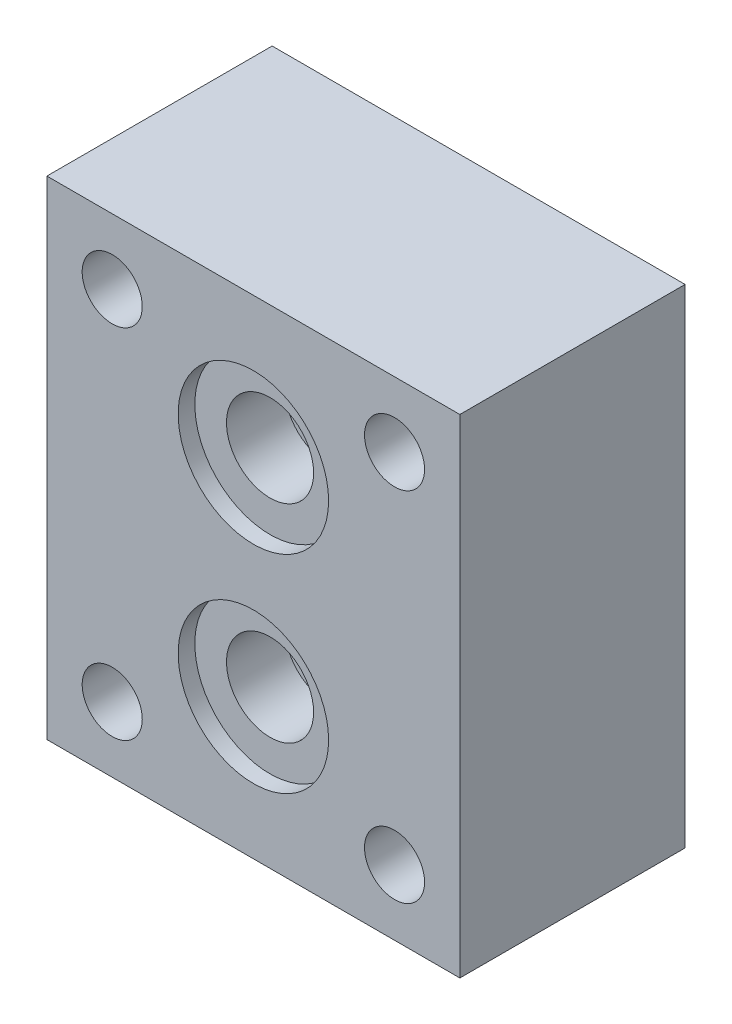
SolidWorks part; units mm, degrees
ref_plane "Front Plane" through (0, 0, 0) normal (1, 0, 0) x (0, 1, 0)
ref_plane "Top Plane" through (0, 0, 0) normal (0, 0, 1) x (0, 1, 0)
ref_plane "Right Plane" through (0, 0, 0) normal (0, 1, 0) x (-1, 0, 0)
sketch "Sketch1" plane through (0, 0, 0) normal (0, 0, 1) x (0, 1, 0)
  line L1 (-41.275, -34.925) -> (41.275, -34.925)
  line L2 (-41.275, -34.925) -> (-41.275, 34.925)
  line L3 (-41.275, 34.925) -> (41.275, 34.925)
  line L4 (41.275, -34.925) -> (41.275, 34.925)
  line L5 (-41.275, -34.925) -> (41.275, 34.925) construction
  line L6 (-41.275, 34.925) -> (41.275, -34.925) construction
  point P0 (0, 0)
extrude "Boss-Extrude1" add sketch "Sketch1" along normal mid plane 38.1
sketch "Sketch2" plane through (0, 0, 0) normal (0, 0, 1) x (0, 1, 0)
  circle A0 centre (-30.226, -23.876) radius 5.08
extrude "Cut-Extrude2" cut sketch "Sketch2" against normal through all from offset 19.05
sketch "Sketch3" plane through (0, 0, 0) normal (0, 0, 1) x (0, 1, 0)
  circle A0 centre (30.226, -23.876) radius 5.08
  circle A1 centre (-30.226, 23.876) radius 5.08
  circle A2 centre (30.226, 23.876) radius 5.08
extrude "Cut-Extrude4" cut sketch "Sketch3" against normal through all from offset 19.05
sketch "Sketch4" plane through (0, 0, 0) normal (0, 0, 1) x (0, 1, 0)
  circle A0 centre (-17.526, 0) radius 7.366
extrude "Cut-Extrude6" cut sketch "Sketch4" against normal blind 12.7 from offset 19.05
sketch "Sketch5" plane through (0, 0, 0) normal (0, 0, 1) x (0, 1, 0)
  circle A0 centre (-17.526, 0) radius 12.7254
extrude "Cut-Extrude8" cut sketch "Sketch5" against normal blind 2.8194 from offset 19.05
sketch "Sketch6" plane through (0, 0, 0) normal (0, 0, 1) x (0, 1, 0)
  circle A0 centre (17.526, 0) radius 7.366
extrude "Cut-Extrude10" cut sketch "Sketch6" against normal blind 12.7 from offset 19.05
sketch "Sketch7" plane through (0, 0, 0) normal (0, 0, 1) x (0, 1, 0)
  circle A0 centre (17.526, 0) radius 12.7254
extrude "Cut-Extrude12" cut sketch "Sketch7" against normal blind 2.8194 from offset 19.05
